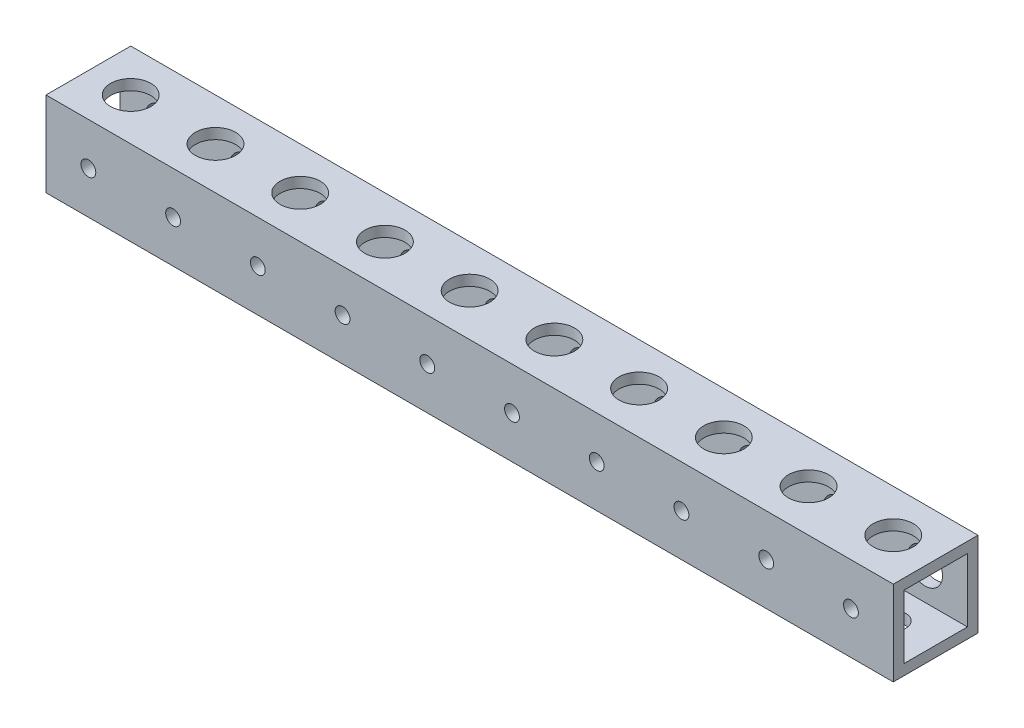
SolidWorks part; units mm, degrees
ref_plane "Front Plane" through (0, 0, 0) normal (0, 0, 1) x (1, 0, 0)
ref_plane "Top Plane" through (0, 0, 0) normal (0, 1, 0) x (1, 0, 0)
ref_plane "Right Plane" through (0, 0, 0) normal (1, 0, 0) x (0, 0, -1)
sketch "Sketch2" plane through (0, 0, 0) normal (1, 0, 0) x (0, 0, -1)
  line L1 (-12.7, -12.7) -> (12.7, -12.7)
  line L2 (-12.7, -12.7) -> (-12.7, 12.7)
  line L3 (-12.7, 12.7) -> (12.7, 12.7)
  line L4 (12.7, -12.7) -> (12.7, 12.7)
  line L5 (-12.7, -12.7) -> (12.7, 12.7) construction
  line L6 (-12.7, 12.7) -> (12.7, -12.7) construction
  line L7 (-9.525, -9.525) -> (9.525, -9.525)
  line L8 (-9.525, -9.525) -> (-9.525, 9.525)
  line L9 (-9.525, 9.525) -> (9.525, 9.525)
  line L10 (9.525, -9.525) -> (9.525, 9.525)
  line L11 (-9.525, -9.525) -> (9.525, 9.525) construction
  line L12 (-9.525, 9.525) -> (9.525, -9.525) construction
  point P0 (0, 0)
  point P6 (0, 0)
  dimension "D1" = 25.4
  dimension "D2" = 25.4
  dimension "D3" = 3.175
extrude "Boss-Extrude1" add sketch "Sketch2" along normal blind 254
sketch "Sketch3" plane through (0, 12.7, 0) normal (0, 1, 0) x (1, 0, 0)
  line L0 (0, 12.7) -> (0, -12.7) construction
  line L2 (254, 12.7) -> (0, 12.7) construction
  circle A0 centre (12.7, 0) radius 6.0325
  point P6 (0, 0)
  dimension "D1" = 12.7
  dimension "D2" = 12.065
  dimension "D3" = 12.7
extrude "Cut-Extrude1" cut sketch "Sketch3" against normal blind 3.175
sketch "Sketch4" plane through (0, -12.7, 0) normal (0, -1, 0) x (1, 0, 0)
  line L0 (0, 12.7) -> (0, -12.7) construction
  line L1 (254, 12.7) -> (0, 12.7) construction
  circle A0 centre (12.7, 0) radius 3.81
  dimension "D2" = 7.62
  dimension "D1" = 12.7
  dimension "D3" = 12.7
extrude "Cut-Extrude2" cut sketch "Sketch4" against normal blind 3.175
pattern_linear "LPattern1" count 10 spacing 25.4 along (1, 0, 0) of "Cut-Extrude2", "Cut-Extrude1"
sketch "Sketch6" plane through (0, 0, 12.7) normal (0, 0, 1) x (1, 0, 0)
  line L0 (254, -12.7) -> (0, -12.7) construction
  circle A0 centre (12.7, 0) radius 2.2225
  dimension "D3" = 4.445
  dimension "D1" = 12.7
  dimension "D2" = 12.7
extrude "Cut-Extrude3" cut sketch "Sketch6" against normal blind 3.175
sketch "Sketch7" plane through (0, 0, -12.7) normal (0, 0, -1) x (-1, 0, 0)
  line L0 (0, -12.7) -> (0, 12.7) construction
  line L2 (-254, 12.7) -> (0, 12.7) construction
  circle A0 centre (-12.7, 0) radius 5.2387
  point P8 (-12.0024, 4.3702)
  dimension "D3" = 10.4775
  dimension "D1" = 12.7
  dimension "D2" = 12.7
extrude "Cut-Extrude4" cut sketch "Sketch7" against normal blind 3.175
pattern_linear "LPattern2" count 10 spacing 25.4 along (1, 0, 0) of "Cut-Extrude4", "Cut-Extrude3"
